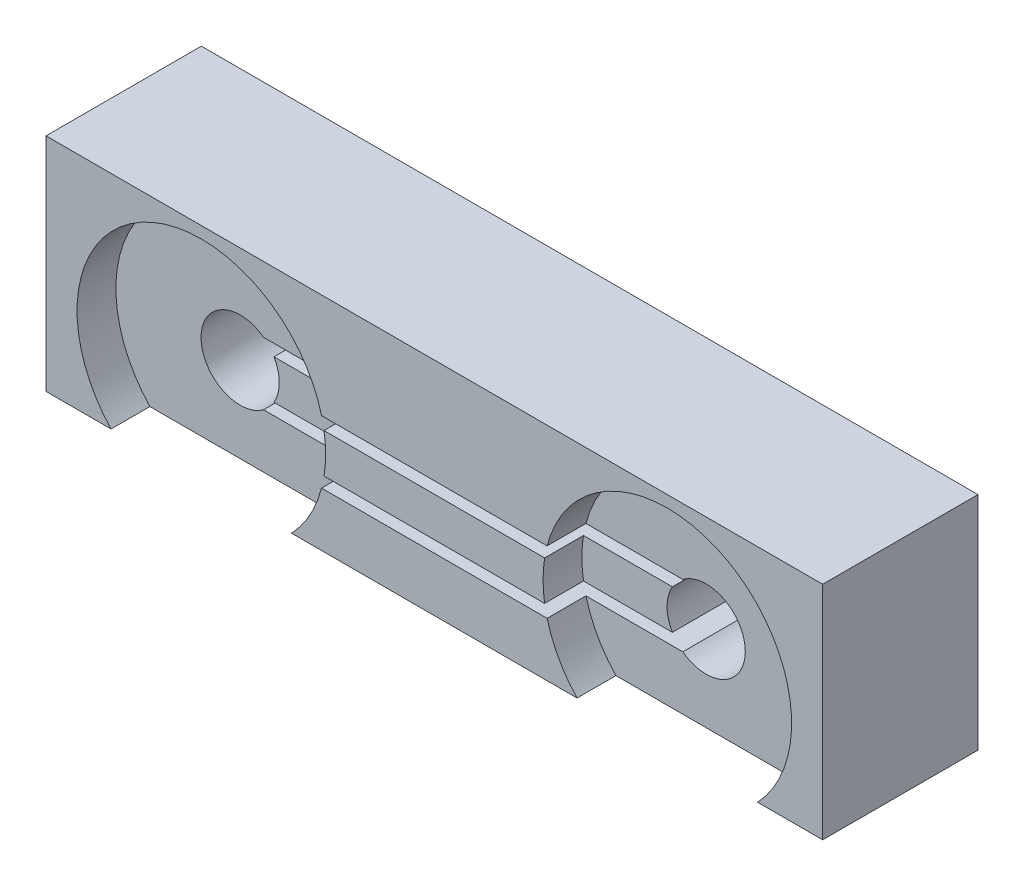
SolidWorks part; units mm, degrees
ref_plane "Front Plane" through (0, 0, 0) normal (0, 0, 1) x (1, 0, 0)
ref_plane "Top Plane" through (0, 0, 0) normal (0, 1, 0) x (1, 0, 0)
ref_plane "Right Plane" through (0, 0, 0) normal (1, 0, 0) x (0, 0, -1)
sketch "Sketch1" plane through (0, 0, 0) normal (0, 0, 1) x (1, 0, 0)
  line L1 (-100, -35) -> (100, -35)
  line L2 (-100, -35) -> (-100, 35)
  line L3 (-100, 35) -> (100, 35)
  line L4 (100, -35) -> (100, 35)
  line L5 (-100, -35) -> (100, 35) construction
  line L6 (-100, 35) -> (100, -35) construction
  point P0 (0, 0)
  dimension "D1" = 200
  dimension "D2" = 70
extrude "Boss-Extrude1" add sketch "Sketch1" along normal blind 40
sketch "Sketch2" plane through (0, 0, 40) normal (0, 0, 1) x (1, 0, 0)
  line L0 (0, 0) -> (0, 50000) construction
  circle A0 centre (60, 0) radius 2.75
  circle A1 centre (-60, 0) radius 2.75
  point P2 (0, 0)
  dimension "D1" = 5.5
  dimension "D2" = 60
extrude "ShaftFits" cut sketch "Sketch2" against normal up to next
sketch "Sketch3" plane through (0, 0, 40) normal (0, 0, 1) x (1, 0, 0)
  line L0 (0, 0) -> (0, 50000) construction
  circle A0 centre (60, 0) radius 8.075
  circle A1 centre (-60, 0) radius 8.075
  dimension "D1" = 16.15
extrude "Pulley" cut sketch "Sketch3" against normal blind 30
sketch "Sketch4" plane through (0, 0, 40) normal (0, 0, 1) x (1, 0, 0)
  line L0 (0, 0) -> (0, 50000) construction
  circle A0 centre (60, 0) radius 30
  circle A1 centre (-60, 0) radius 30
  dimension "D1" = 60
extrude "Gears fits" cut sketch "Sketch4" against normal blind 10
sketch "Sketch5" plane through (0, 0, 40) normal (0, 0, 1) x (1, 0, 0)
  line L0 (100, -35) -> (100, 35) construction
  line L1 (-100, -35) -> (100, -35)
  line L2 (-100, -35) -> (-100, -22)
  line L3 (-100, -22) -> (100, -22)
  line L4 (100, -35) -> (100, -22)
  circle A0 centre (60, 0) radius 30 construction
  dimension "D1" = 22
extrude "Gear letout" cut sketch "Sketch5" against normal up to next
sketch "Sketch8" plane through (0, 0, 40) normal (0, 0, 1) x (1, 0, 0)
  line L0 (0, 0) -> (-50000, 0) construction
  line L1 (-60, 5.075) -> (60, 5.075)
  line L2 (-60, 5.075) -> (-60, 8.075)
  line L3 (-60, 8.075) -> (60, 8.075)
  line L4 (60, 5.075) -> (60, 8.075)
  line L5 (60, -5.075) -> (60, -8.075)
  line L6 (-60, -8.075) -> (60, -8.075)
  line L7 (-60, -5.075) -> (-60, -8.075)
  line L8 (-60, -5.075) -> (60, -5.075)
  circle A0 centre (-60, 0) radius 8.075 construction
  point P9 (-60, 0)
  point P10 (60, 0)
  dimension "D1" = 3
extrude "Closed-loop timing belt" cut sketch "Sketch8" against normal up to surface (30 mm away) up to face at (-68.075, 0, 10)
sketch "Sketch6" plane through (0, 0, 40) normal (0, 0, 1) x (1, 0, 0)
  line L0 (0, 0) -> (0, 50000) construction
  circle A0 centre (60, 0) radius 32
  arc A1 (80.3961, -22) -> (31.1072, 8.075) centre (60, 0) ccw construction
  circle A2 centre (-60, 0) radius 32
  dimension "D1" = 2
extrude "Gear margin" cut sketch "Sketch6" against normal up to surface (10 mm away) up to face at (-54.8665, -2.0028, 30)
sketch "Sketch7" plane through (0, 0, 30) normal (0, 0, 1) x (1, 0, 0)
  line L0 (0, 0) -> (0, 50000) construction
  circle A0 centre (60, 0) radius 10.075
  circle A1 centre (60, 0) radius 8.075 construction
  circle A2 centre (-60, 0) radius 10.075
  dimension "D1" = 2
extrude "Pulley margin" cut sketch "Sketch7" against normal up to surface (20 mm away) up to face at (0, 0, 10)
